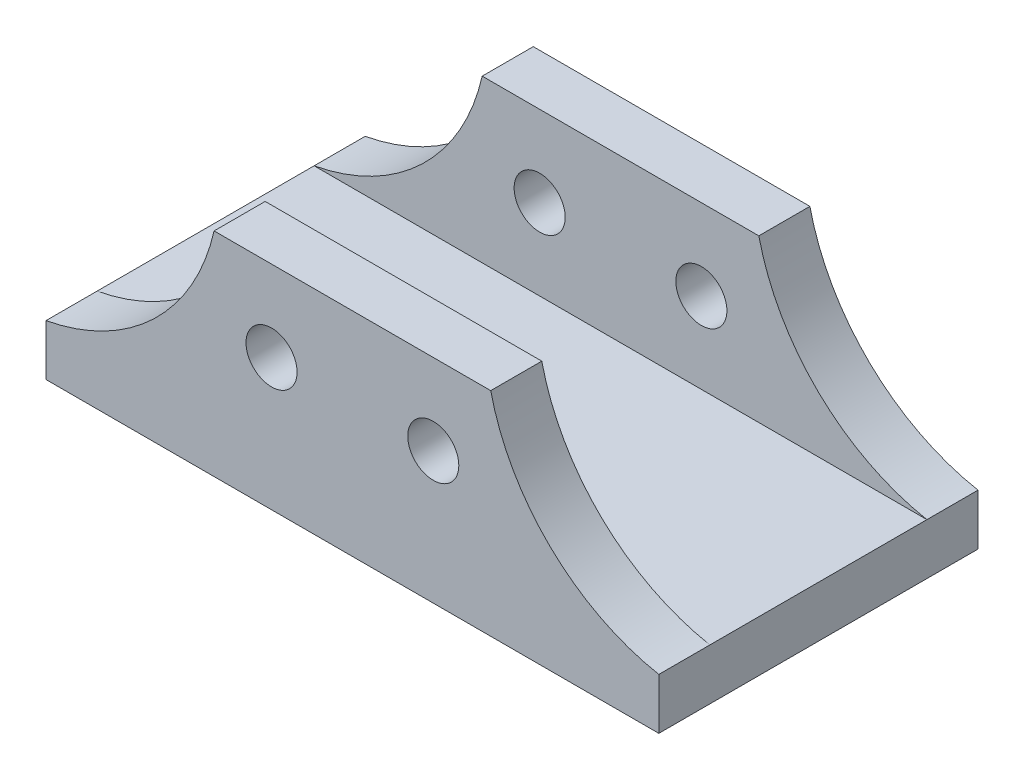
SolidWorks part; units mm, degrees
ref_plane "Płaszczyzna przednia" through (0, 0, 0) normal (0, 0, 1) x (1, 0, 0)
ref_plane "Płaszczyzna górna" through (0, 0, 0) normal (0, 1, 0) x (1, 0, 0)
ref_plane "Płaszczyzna prawa" through (0, 0, 0) normal (1, 0, 0) x (0, 0, -1)
sketch "Szkic1" plane through (0, 0, 0) normal (0, 0, 1) x (1, 0, 0)
  line L0 (0, 50) -> (0, 0) construction
  line L1 (-72, 0) -> (72, 0)
  line L2 (72, 0) -> (72, 12)
  line L3 (-32.5, 50) -> (32.5, 50)
  line L4 (-72, 0) -> (-72, 12)
  arc A0 (72, 12) -> (32.5, 50) centre (81.2436, 61.1381) cw
  circle A1 centre (19, 31) radius 6
  circle A2 centre (-19, 31) radius 6
  arc A3 (-72, 12) -> (-32.5, 50) centre (-81.2436, 61.1381) ccw
  point P9 (0, 0)
  point P10 (0, 0)
  point P11 (0, 0)
  dimension "D5" = 50
  dimension "D6" = 12
  dimension "D1" = 72
  dimension "D2" = 12
  dimension "D3" = 32.5
  dimension "D4" = 50
  dimension "D7" = 19
  dimension "D8" = 31
extrude "Dodanie-wyciągnięcie1" add sketch "Szkic1" along normal blind 12
ref_plane "Płaszczyzna1" through (0, 0, 37.5) normal (0, 0, 1) x (1, 0, 0)
mirror "Lustro2" about plane through (0, 0, 37.5) normal (0, 0, 1) of bodies 101
sketch "Szkic2" plane through (0, 0, 37.5) normal (0, 0, 1) x (1, 0, 0)
  line L1 (-72, 0) -> (72, 0)
  line L2 (-72, 0) -> (-72, 12)
  line L3 (-72, 12) -> (72, 12)
  line L4 (72, 0) -> (72, 12)
extrude "Dodanie-wyciągnięcie2" add sketch "Szkic2" along normal up to surface and the other way up to surface
